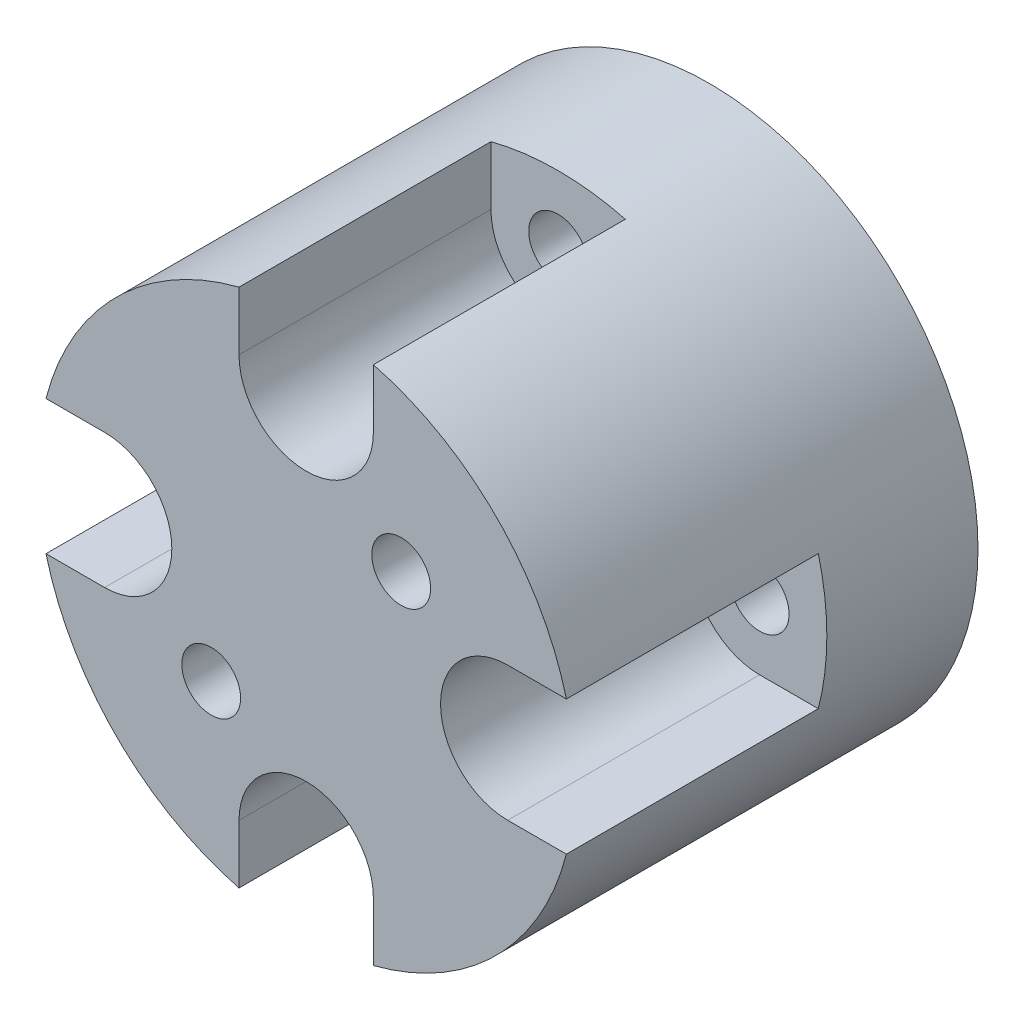
SolidWorks part; units mm, degrees
ref_plane "Front Plane" through (0, 0, 0) normal (0, 0, 1) x (1, 0, 0)
ref_plane "Top Plane" through (0, 0, 0) normal (0, 1, 0) x (1, 0, 0)
ref_plane "Right Plane" through (0, 0, 0) normal (1, 0, 0) x (0, 0, -1)
sketch "Sketch1" plane through (0, 0, 0) normal (0, 0, 1) x (1, 0, 0)
  line L0 (0, 12) -> (0, 0) construction
  line L1 (0, 0) -> (12, 0) construction
  circle A0 centre (0, 0) radius 16
  circle A2 centre (0, 12) radius 1.75
  circle A3 centre (12, 0) radius 1.75
  circle A4 centre (-12, 0) radius 1.75
  circle A5 centre (0, -12) radius 1.75
  dimension "D1" = 32
  dimension "D2" = 3.5
  dimension "D3" = 12
  dimension "D4" = 3.5
  dimension "D5" = 12
extrude "Boss-Extrude1" add sketch "Sketch1" along normal blind 24
sketch "Sketch2" plane through (0, 0, 0) normal (0, 0, -1) x (-1, 0, 0)
  line L0 (0, 0) -> (-9.2218, 9.2218) construction
  line L1 (0, 0) -> (6.9326, 0) construction
  line L2 (0, 0) -> (5.6031, 5.6031) construction
  circle A0 centre (-5.6569, 5.6569) radius 1.75
  circle A1 centre (5.6569, -5.6569) radius 1.75
  dimension "D2" = 3.5
  dimension "D3" = 8
  dimension "D1" = 45
extrude "Cut-Extrude1" cut sketch "Sketch2" against normal through all
sketch "Sketch3" plane through (0, 0, 0) normal (0, 0, -1) x (-1, 0, 0)
  circle A0 centre (-5.6569, 5.6569) radius 4
  circle A1 centre (5.6569, -5.6569) radius 4
  dimension "D1" = 8
  dimension "D2" = 8
extrude "Cut-Extrude2" cut sketch "Sketch3" against normal blind 15
sketch "Sketch4" plane through (0, 0, 24) normal (0, 0, 1) x (1, 0, 0)
  line L0 (-4, 12) -> (-4, 19.5275)
  line L1 (-4, 19.5275) -> (4, 19.5275)
  line L2 (4, 19.5275) -> (4, 12)
  line L3 (12, 4) -> (20.3198, 4)
  line L4 (20.3198, 4) -> (20.3198, -4)
  line L5 (20.3198, -4) -> (12, -4)
  line L6 (-12, 4) -> (-20.8607, 4)
  line L7 (-20.8607, 4) -> (-20.8607, -4)
  line L8 (-20.8607, -4) -> (-12, -4)
  line L9 (-4, -12) -> (-4, -17.6097)
  line L10 (-4, -17.6097) -> (4, -17.6097)
  line L11 (4, -17.6097) -> (4, -12)
  arc A0 (-4, 12) -> (4, 12) centre (0, 12) ccw
  arc A1 (-12, -4) -> (-12, 4) centre (-12, 0) ccw
  arc A2 (12, 4) -> (12, -4) centre (12, 0) ccw
  arc A3 (4, -12) -> (-4, -12) centre (0, -12) ccw
  dimension "D1" = 8
  dimension "D2" = 8
  dimension "D3" = 8
  dimension "D4" = 8
extrude "Cut-Extrude3" cut sketch "Sketch4" against normal blind 15
